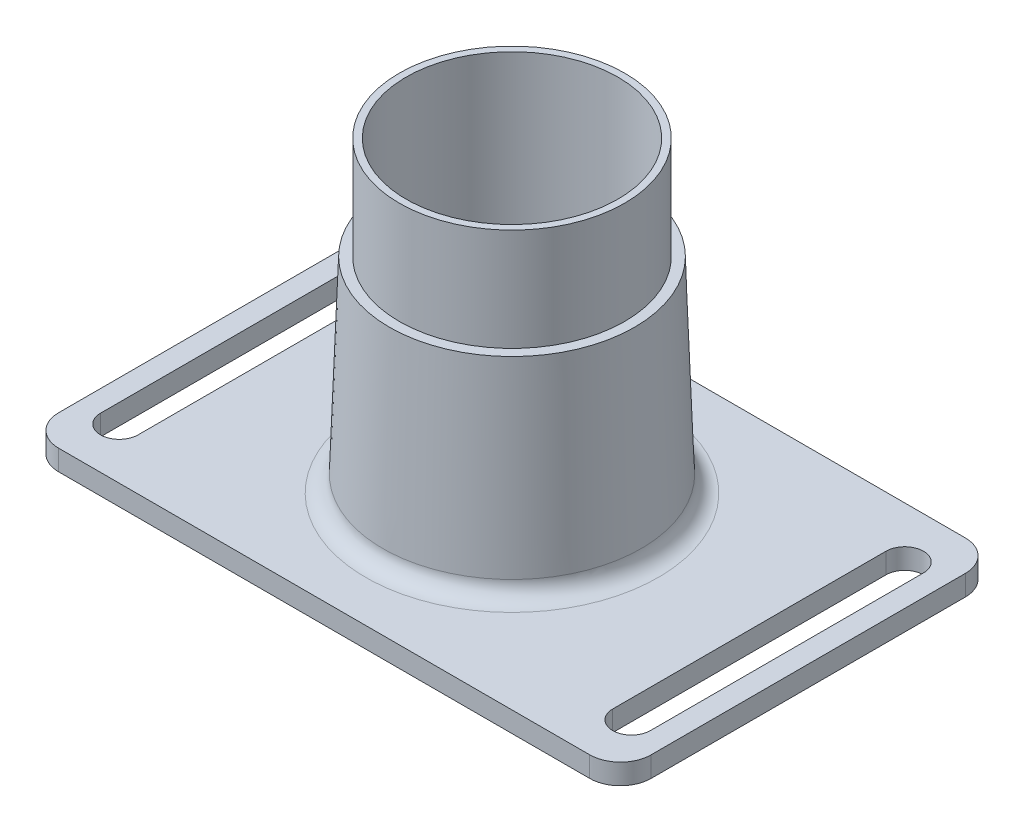
SolidWorks part; units mm, degrees
ref_plane "Front Plane" through (0, 0, 0) normal (0, 0, 1) x (1, 0, 0)
ref_plane "Top Plane" through (0, 0, 0) normal (0, 1, 0) x (1, 0, 0)
ref_plane "Right Plane" through (0, 0, 0) normal (1, 0, 0) x (0, 0, -1)
sketch "Sketch1" plane through (0, 0, 0) normal (0, 1, 0) x (1, 0, 0)
  line L0 (-43.375, 0) -> (43.375, 0) construction
  line L1 (-43.375, -27.5) -> (43.375, -27.5)
  line L2 (-43.375, -27.5) -> (-43.375, 27.5)
  line L3 (-43.375, 27.5) -> (43.375, 27.5)
  line L4 (43.375, -27.5) -> (43.375, 27.5)
  line L5 (0, 27.5) -> (0, -27.5) construction
  line L6 (37.5, 27.5) -> (37.5, -27.5) construction
  line L7 (-37.5, 27.5) -> (-37.5, -27.5) construction
  line L8 (-43.375, 20) -> (43.375, 20) construction
  line L9 (-43.375, -20) -> (43.375, -20) construction
  line L10 (-37.5, 20) -> (-37.5, -20) construction
  line L11 (-34.75, 20) -> (-34.75, -20)
  line L12 (-40.25, 20) -> (-40.25, -20)
  line L13 (37.5, 20) -> (37.5, -20) construction
  line L14 (40.25, 20) -> (40.25, -20)
  line L15 (34.75, 20) -> (34.75, -20)
  circle A0 centre (0, 0) radius 5.5
  arc A1 (-34.75, 20) -> (-40.25, 20) centre (-37.5, 20) ccw
  arc A2 (-40.25, -20) -> (-34.75, -20) centre (-37.5, -20) ccw
  arc A3 (40.25, 20) -> (34.75, 20) centre (37.5, 20) ccw
  arc A4 (34.75, -20) -> (40.25, -20) centre (37.5, -20) ccw
  point P21 (-37.5, 0)
  point P26 (37.5, 0)
  dimension "D3" = 11
  dimension "D8" = 2.75
  dimension "D9" = 2.75
  dimension "D1" = 86.75
  dimension "D2" = 55
  dimension "D4" = 37.5
  dimension "D5" = 37.5
  dimension "D6" = 20
  dimension "D7" = 20
extrude "Boss-Extrude1" add sketch "Sketch1" against normal blind 3
sketch "Sketch4" plane through (0, 0, 0) normal (0, 1, 0) x (1, 0, 0)
  line L1 (-43.375, -27.5) -> (43.375, -27.5)
  line L2 (-43.375, -27.5) -> (-43.375, 27.5)
  line L3 (-43.375, 27.5) -> (43.375, 27.5)
  line L4 (43.375, -27.5) -> (43.375, 27.5)
  line L5 (-43.375, -27.5) -> (43.375, -27.5) construction
  line L6 (-43.375, 27.5) -> (-43.375, -27.5) construction
  line L7 (43.375, -27.5) -> (43.375, 27.5) construction
  line L8 (43.375, 27.5) -> (-43.375, 27.5) construction
  line L10 (40.375, -24.5) -> (-40.375, -24.5)
  line L11 (40.375, -24.5) -> (40.375, 24.5)
  line L12 (40.375, 24.5) -> (-40.375, 24.5)
  line L13 (-40.375, -24.5) -> (-40.375, 24.5)
  dimension "D1" = 3
  dimension "D2" = 3
  dimension "D3" = 3
  dimension "D4" = 3
fillet "Fillet1" radius 4.5 4 edges at (43.375, -1.5, -27.5) (43.375, -1.5, 27.5) (-43.375, -1.5, 27.5) (-43.375, -1.5, -27.5)
sketch "Sketch6" plane through (0, 0, 0) normal (0, 1, 0) x (1, 0, 0)
  circle A0 centre (0, 0) radius 15.5
  circle A1 centre (0, 0) radius 19
  dimension "D1" = 31
  dimension "D2" = 38
extrude "Boss-Extrude3" add sketch "Sketch6" along normal blind 45
sketch "Sketch9" plane through (0, 0, 0) normal (0, 1, 0) x (1, 0, 0)
  line L0 (-30.1887, -24.5) -> (-1.5, -24.5) construction
  line L1 (-38.875, -27.5) -> (38.875, -27.5) construction
  line L2 (-65.1272, 24.5) -> (69.0124, 24.5) construction
  line L3 (38.875, 27.5) -> (-38.875, 27.5) construction
  line L4 (-31.75, -54.4389) -> (-31.75, -1.5) construction
  line L5 (-34.75, -20) -> (-34.75, 20) construction
  line L6 (31.75, -48.4416) -> (31.75, 54.4882) construction
  line L7 (43.375, -23) -> (43.375, 23) construction
  line L8 (34.75, 20) -> (34.75, -20) construction
  line L21 (0, -35.2504) -> (0, 38.5596) construction
  line L29 (-31.75, -22.38) -> (-31.75, -1.5)
  line L30 (-31.75, -22.38) -> (-7.1805, -3.5271)
  line L31 (-31.75, 22.38) -> (-7.1805, 3.5271)
  line L34 (-29.63, -24.5) -> (-1.5, -24.5)
  line L35 (-29.63, -24.5) -> (-5.397, -5.9053)
  line L36 (29.63, -24.5) -> (5.397, -5.9053)
  line L37 (-53.7207, 0) -> (64.1745, 0) construction
  line L41 (1.5, -24.5) -> (52.6932, -24.5) construction
  line L43 (-1.5, -24.5) -> (-1.5, -7.8581)
  line L45 (1.5, -24.5) -> (1.5, -7.8581)
  line L46 (1.5, -24.5) -> (29.63, -24.5)
  line L47 (-31.75, 1.5) -> (-31.75, 46.7242) construction
  line L48 (-31.75, -1.5) -> (-7.8581, -1.5)
  line L50 (-31.75, 1.5) -> (-7.8581, 1.5)
  line L52 (-31.75, 1.5) -> (-31.75, 22.38)
  line L53 (1.5, 24.5) -> (1.5, 7.8581)
  line L54 (1.5, 24.5) -> (29.63, 24.5)
  line L55 (29.63, 24.5) -> (5.397, 5.9053)
  line L56 (-29.63, 24.5) -> (-5.397, 5.9053)
  line L57 (-1.5, 24.5) -> (-1.5, 7.8581)
  line L58 (-29.63, 24.5) -> (-1.5, 24.5)
  line L59 (31.75, 1.5) -> (31.75, 22.38)
  line L60 (31.75, 1.5) -> (7.8581, 1.5)
  line L61 (31.75, 22.38) -> (7.1805, 3.5271)
  line L62 (31.75, -22.38) -> (7.1805, -3.5271)
  line L63 (31.75, -1.5) -> (7.8581, -1.5)
  line L64 (31.75, -22.38) -> (31.75, -1.5)
  arc A0 (-7.1805, -3.5271) -> (-7.8581, -1.5) centre (0, 0) cw
  arc A2 (-5.397, -5.9053) -> (-1.5, -7.8581) centre (0, 0) ccw
  arc A4 (1.5, -7.8581) -> (5.397, -5.9053) centre (0, 0) ccw
  arc A5 (-7.8581, 1.5) -> (-7.1805, 3.5271) centre (0, 0) cw
  arc A6 (1.5, 7.8581) -> (5.397, 5.9053) centre (0, 0) cw
  arc A7 (-5.397, 5.9053) -> (-1.5, 7.8581) centre (0, 0) cw
  arc A8 (7.8581, 1.5) -> (7.1805, 3.5271) centre (0, 0) ccw
  arc A9 (7.1805, -3.5271) -> (7.8581, -1.5) centre (0, 0) ccw
  dimension "D17" = 8
  dimension "D13" = 8
  dimension "D1" = 3
  dimension "D2" = 3
  dimension "D3" = 3
  dimension "D4" = 3
  dimension "D5" = 2.12
  dimension "D6" = 2.12
  dimension "D7" = 127.5
  dimension "D8" = 127.5
  dimension "D9" = 142.5
  dimension "D10" = 142.5
  dimension "D11" = 2.12
  dimension "D12" = 2.12
  dimension "D14" = 3
  dimension "D15" = 1.5
  dimension "D16" = 3
  dimension "D18" = 1.5
extrude "Cut-Extrude1" cut sketch "Sketch9" against normal up to next from offset 1 offset against normal yes
ref_plane "Plane1" through (0, 30, 0) normal (0, 1, 0) x (1, 0, 0)
sketch "Sketch12" plane through (0, 30, 0) normal (0, 1, 0) x (1, 0, 0)
  circle A0 centre (0, 0) radius 16.5
  circle A1 centre (0, 0) radius 19
  dimension "D1" = 33
  dimension "D2" = 38
extrude "Cut-Extrude3" cut sketch "Sketch12" along normal up to next
cosmetic thread "Cosmetic Thread2" parameters "D1"=15, "D2"=29.158
draft "Draft8" type of draft neutral plane draft angle 2 faces to draft 1 face at (0, 0, -19) neutral plane through (0, 0, 0) neutral plane normal (0, 1, 0) parameters "D1"=2
fillet "Fillet3" radius 2.5 1 edges at (0, 0, -19)
